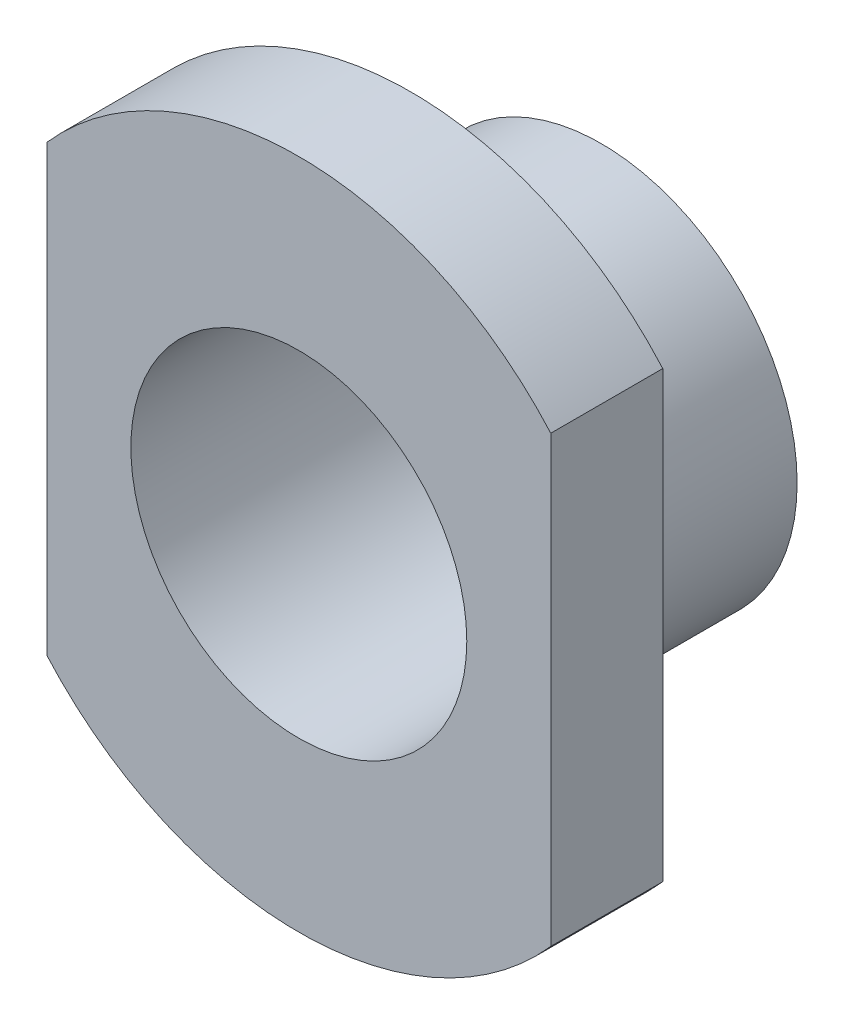
SolidWorks part; units mm, degrees
ref_plane "前视基准面" through (0, 0, 0) normal (0, 0, 1) x (1, 0, 0)
ref_plane "上视基准面" through (0, 0, 0) normal (0, 1, 0) x (1, 0, 0)
ref_plane "右视基准面" through (0, 0, 0) normal (1, 0, 0) x (0, 0, -1)
other "Configuration Table"
sketch "草图1" plane through (0, 0, 0) normal (0, 0, 1) x (1, 0, 0)
  circle A0 centre (0, 0) radius 1.75
  circle A1 centre (0, 0) radius 1.5
  dimension "D1" = 3.5
  dimension "D2" = 3
extrude "凸台-拉伸1" add sketch "草图1" along normal blind 1.7
sketch "草图2" plane through (0, 0, 1.7) normal (0, 0, 1) x (1, 0, 0)
  line L1 (-2.25, -3) -> (2.25, -3)
  line L2 (-2.25, -3) -> (-2.25, 3)
  line L3 (-2.25, 3) -> (2.25, 3)
  line L4 (2.25, -3) -> (2.25, 3)
  line L5 (-2.25, -3) -> (2.25, 3) construction
  line L6 (-2.25, 3) -> (2.25, -3) construction
  circle A0 centre (0, 0) radius 3
  circle A1 centre (0, 0) radius 1.5 construction
  circle A2 centre (0, 0) radius 1.5
  circle M6 centre (0, 0) radius 1.75
  circle M7 centre (0, 0) radius 1.5
  dimension "D1" = 6
  dimension "D2" = 4.5
extrude "凸台-拉伸2" add sketch "草图2" along normal blind 1 contours L4 A0 L2 M6 | M6 M7
